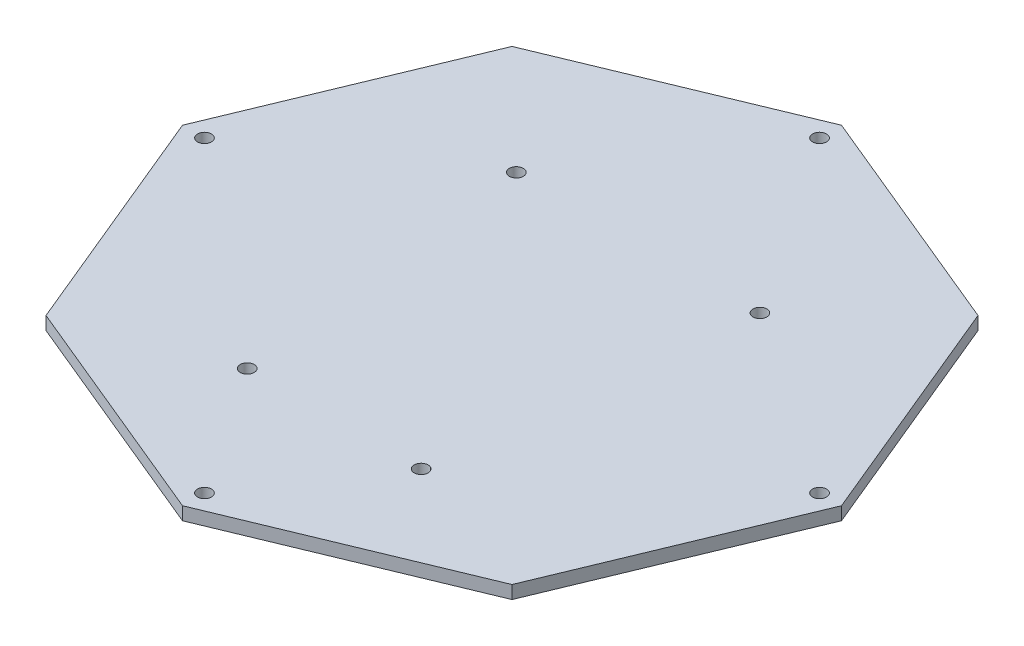
SolidWorks part; units mm, degrees
ref_plane "Front Plane" through (0, 0, 0) normal (0, 0, 1) x (1, 0, 0)
ref_plane "Top Plane" through (0, 0, 0) normal (0, 1, 0) x (1, 0, 0)
ref_plane "Right Plane" through (0, 0, 0) normal (1, 0, 0) x (0, 0, -1)
sketch "Sketch1" plane through (0, 0, 0) normal (0, 1, 0) x (1, 0, 0)
  line L0 (0, -75.7675) -> (53.5757, -53.5757)
  line L7 (0, 75.7675) -> (-53.5757, 53.5757)
  line L8 (-53.5757, 53.5757) -> (-75.7675, 0)
  line L9 (-75.7675, 0) -> (-53.5757, -53.5757)
  line L10 (-53.5757, -53.5757) -> (0, -75.7675)
  line L11 (53.5757, -53.5757) -> (75.7675, 0)
  line L12 (75.7675, 0) -> (53.5757, 53.5757)
  line L13 (53.5757, 53.5757) -> (0, 75.7675)
  circle A0 centre (0, 0) radius 70 construction
  dimension "D1" = 140
extrude "Boss-Extrude2" add sketch "Sketch1" along normal blind 3
sketch "Sketch3" plane through (0, 3, 0) normal (0, 1, 0) x (1, 0, 0)
  line L0 (-75.7675, 0) -> (75.7675, 0) construction
  line L1 (0, 75.7675) -> (0, -75.7675) construction
  circle A4 centre (-70.7107, 0) radius 1.6
  circle A5 centre (0, 70.7107) radius 1.6
  circle A6 centre (70.7107, 0) radius 1.6
  circle A7 centre (0, -70.7107) radius 1.6
  point P28 (0, 0)
  dimension "D4" = 3.2
  dimension "D6" = 100
  dimension "D5" = 4
extrude "Cut-Extrude3" cut sketch "Sketch3" against normal through all both and the other way through all
sketch "Sketch4" plane through (0, 3, 0) normal (0, 1, 0) x (1, 0, 0)
  line L0 (-28, 29) -> (20.1084, -41) construction
  line L1 (-28, 29) -> (28, 29) construction
  line L2 (0, 29) -> (0, 0) construction
  circle A0 centre (-19.8916, -41) radius 1.6
  circle A1 centre (20.1084, -41) radius 1.6
  circle A2 centre (-28, 29) radius 1.6
  circle A3 centre (28, 29) radius 1.6
  point P10 (0, 0)
  dimension "D5" = 3.2
  dimension "D1" = 56
  dimension "D2" = 40
  dimension "D3" = 70
  dimension "D4" = 29
extrude "Cut-Extrude4" cut sketch "Sketch4" against normal through all both and the other way through all
